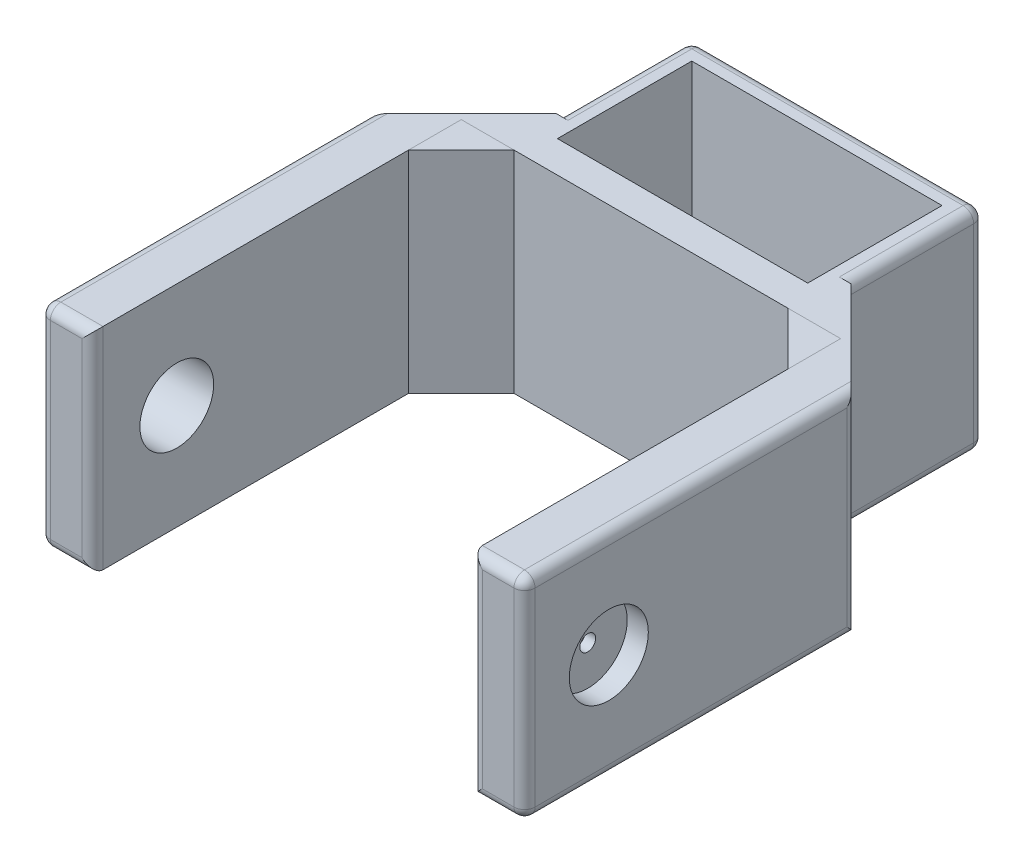
SolidWorks part; units mm, degrees
ref_plane "Front Plane" through (0, 0, 0) normal (0, 0, 1) x (1, 0, 0)
ref_plane "Top Plane" through (0, 0, 0) normal (0, 1, 0) x (1, 0, 0)
ref_plane "Right Plane" through (0, 0, 0) normal (1, 0, 0) x (0, 0, -1)
sketch "Sketch2" plane through (0, 0, 0) normal (0, 1, 0) x (1, 0, 0)
  line L12 (-23, 0) -> (23, 0)
  line L13 (23, 0) -> (23, -40)
  line L14 (23, -40) -> (18, -40)
  line L15 (18, -40) -> (18, -5)
  line L16 (18, -5) -> (-18, -5)
  line L17 (-18, -5) -> (-18, -40)
  line L18 (-18, -40) -> (-23, -40)
  line L19 (-23, -40) -> (-23, 0)
  point P4 (0, 0)
  dimension "D2" = 5
  dimension "36" = 36
  dimension "D3" = 5
  dimension "D4" = 5
  dimension "D6" = 35
extrude "Boss-Extrude1" add sketch "Sketch2" along normal blind 20
sketch "Sketch6" plane through (0, 0, 0) normal (1, 0, 0) x (0, 0, -1)
  circle A0 centre (-32, 10) radius 3.5
extrude "Cut-Extrude1" cut sketch "Sketch6" against normal through all contours A0
sketch "Sketch7" plane through (0, 0, 0) normal (1, 0, 0) x (0, 0, -1)
  line L5 (-32, 14.25) -> (-17, 12.5)
  line L6 (-32, 6.25) -> (-17, 8)
  arc A0 (-32, 14.25) -> (-32, 6.25) centre (-32, 10.25) ccw
  arc A1 (-17, 8) -> (-17, 12.5) centre (-17, 10.25) ccw
  point P7 (-32, 10.25)
  point P11 (-17, 10.25)
  dimension "D1" = 4.5
extrude "Cut-Extrude5" cut sketch "Sketch7" against normal blind 0.0001 and the other way blind 20
sketch "Sketch9" plane through (0, 0, 0) normal (0, 1, 0) x (1, 0, 0)
  line L8 (23, 0) -> (-23, 0) construction
  line L13 (13.875, 12.75) -> (-13.875, 12.75)
  line L14 (13.875, 12.75) -> (13.875, 0)
  line L15 (13.875, 0) -> (-13.875, 0)
  line L16 (-13.875, 12.75) -> (-13.875, 0)
  line L17 (13.875, 12.75) -> (-13.875, 0) construction
  line L18 (13.875, 0) -> (-13.875, 12.75) construction
  point P0 (0, 6.375)
  dimension "D1" = 27.75
  dimension "D2" = 12.75
  dimension "D3" = 0
extrude "Boss-Extrude2" add sketch "Sketch9" along normal blind 20
ref_plane "Plane1" through (0, 20, 0) normal (0, 1, 0) x (1, 0, 0)
sketch "Sketch10" plane through (0, 20, 0) normal (0, 1, 0) x (1, 0, 0)
  line L2 (-11.875, 10.75) -> (-11.875, -2)
  line L3 (-11.875, -2) -> (11.875, -2)
  line L4 (11.875, 10.75) -> (11.875, -2)
  line L5 (13.875, 0) -> (13.875, 12.75) construction
  line L6 (-13.875, 12.75) -> (-13.875, 0) construction
  line L7 (11.875, 10.75) -> (-11.875, 10.75)
  line L8 (13.875, 12.75) -> (-13.875, 12.75) construction
  dimension "D1" = 2
  dimension "D2" = 2
  dimension "D3" = 2
  dimension "D4" = 12.75
extrude "Cut-Extrude7" cut sketch "Sketch10" against normal blind 18
sketch "Sketch11" plane through (0, 0, 0) normal (0, 1, 0) x (1, 0, 0)
  line L4 (11.875, 10.75) -> (-11.875, 10.75) construction
  line L6 (-13.875, 12.75) -> (-13.875, 0) construction
  circle A0 centre (-5.375, 4.375) radius 3
  dimension "D1" = 6.375
  dimension "D2" = 8.5
extrude "Boss-Extrude3" add sketch "Sketch11" along normal blind 0.001 and the other way blind 7
ref_plane "Plane2" through (-23, 0, 0) normal (-1, 0, 0) x (0, 0, 1)
sketch "Sketch14" plane through (-23, 0, 0) normal (-1, 0, 0) x (0, 0, 1)
  line L0 (0, 0) -> (40, 0) construction
  line L1 (-9.75, 2) -> (0.25, 2)
  line L2 (-9.75, 2) -> (-9.75, 7)
  line L3 (-9.75, 7) -> (0.25, 7)
  line L4 (0.25, 2) -> (0.25, 7)
  line L5 (-9.75, 2) -> (0.25, 7) construction
  line L6 (-9.75, 7) -> (0.25, 2) construction
  line L8 (-12.75, 20) -> (-12.75, 0) construction
  point P0 (-4.75, 4.5)
  dimension "D1" = 2
  dimension "D2" = 5
  dimension "D3" = 10
  dimension "D4" = 3
extrude "Cut-Extrude8" cut sketch "Sketch14" against normal up to surface (11.125 mm away) up to face at (-11.875, 11, -4.375)
ref_plane "Plane3" through (-23, 20, 0) normal (0, -1, 0) x (-1, 0, 0)
ref_plane "Plane4" through (23, 0, 0) normal (1, 0, 0) x (0, 0, -1)
sketch "Sketch15" plane through (23, 0, 0) normal (1, 0, 0) x (0, 0, -1)
  circle A1 centre (-32, 10) radius 3.75
  dimension "D1" = 7.5
extrude "Cut-Extrude9" cut sketch "Sketch15" against normal blind 2
sketch "Sketch16" plane through (23, 0, 0) normal (1, 0, 0) x (0, 0, -1)
  circle A0 centre (-32, 10) radius 0.75
  dimension "D1" = 1.5
extrude "Cut-Extrude10" cut sketch "Sketch16" against normal through all both and the other way through all
ref_plane "Plane5" through (0, 20, 0) normal (0, -1, 0) x (-1, 0, 0)
sketch "Sketch18" plane through (0, 20, 0) normal (0, -1, 0) x (-1, 0, 0)
  line L0 (18, -5) -> (13, -5)
  line L1 (18, -5) -> (-18, -5) construction
  line L2 (18, -5) -> (18, -10)
  line L3 (18, -40) -> (18, -5) construction
  line L4 (-18, -5) -> (-18, -10)
  line L5 (-18, -5) -> (-18, -40) construction
  line L6 (-18, -5) -> (-13, -5)
  line L7 (-18, -10) -> (-13, -5)
  line L8 (18, -10) -> (13, -5)
  dimension "D3" = 5
extrude "Boss-Extrude4" add sketch "Sketch18" along normal blind 20 separate body
chamfer "Chamfer1" distance 9 angle 45 2 edges at (-23, 13.5, 0) (23, 10, 0)
fillet "Fillet3" radius 1 22 edges at (13.875, 10, -12.75) (0, 20, -12.75) (-13.875, 10, -12.75) (0, 0, -12.75) (-23, 10, 40) (-20.5, 0, 40) (-20.5, 20, 40) (-18, 10, 40) (18, 10, 40) (20.5, 0, 40) (20.5, 20, 40) (23, 10, 40) (-13.875, 0, -6.375) (-13.875, 20, -6.375) (13.875, 0, -6.375) (13.875, 20, -6.375) (-23, 10, 9) (23, 10, 9) (-23, 20, 24.5) (-23, 0, 24.5) (23, 0, 24.5) (23, 20, 24.5)
